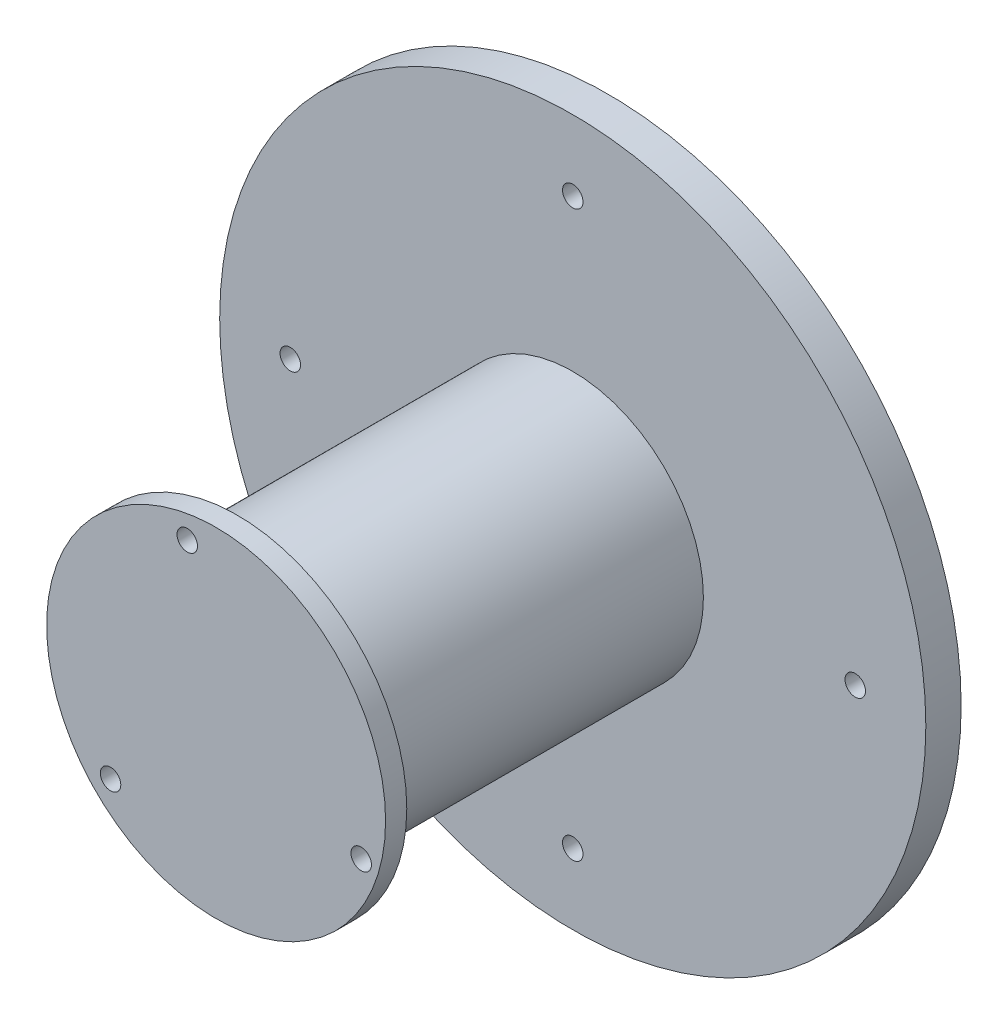
SolidWorks part; units mm, degrees
ref_plane "정면" through (0, 0, 0) normal (0, 0, 1) x (1, 0, 0)
ref_plane "윗면" through (0, 0, 0) normal (0, 1, 0) x (1, 0, 0)
ref_plane "우측면" through (0, 0, 0) normal (1, 0, 0) x (0, 0, -1)
sketch "스케치1" plane through (0, 0, 0) normal (0, 0, 1) x (1, 0, 0)
  line L0 (0, 18.5) -> (0, -18.5) construction
  line L1 (-18.5, 0) -> (18.5, 0) construction
  circle A0 centre (0, 0) radius 18.5
  dimension "D1" = 37
extrude "보스-돌출1" add sketch "스케치1" along normal blind 50
sketch "스케치2" plane through (0, 0, 0) normal (0, 0, -1) x (-1, 0, 0)
  circle A0 centre (0, 0) radius 50
  dimension "D1" = 100
extrude "보스-돌출2" add sketch "스케치2" along normal blind 5
sketch "스케치3" plane through (0, 0, -5) normal (0, 0, -1) x (-1, 0, 0)
  line L0 (0, 50) -> (0, -50) construction
  line L1 (-50, 0) -> (50, 0) construction
  circle A0 centre (0, 0) radius 50 construction
  circle A1 centre (0, 0) radius 25
  circle A2 centre (0, 0) radius 23
  dimension "D1" = 50
  dimension "D2" = 46
extrude "보스-돌출3" add sketch "스케치3" along normal blind 3
sketch "스케치4" plane through (0, 0, -5) normal (0, 0, -1) x (-1, 0, 0)
  circle A2 centre (-40, 0) radius 1.45
  circle A4 centre (40, 0) radius 1.45
  circle A5 centre (0, 40) radius 1.45
  circle A6 centre (0, -40) radius 1.45
  dimension "D2" = 2.9
  dimension "D3" = 2.9
extrude "컷-돌출1" cut sketch "스케치4" against normal blind 23 contours A2 | A5 | A4 | A6
sketch "스케치5" plane through (0, 0, 50) normal (0, 0, 1) x (1, 0, 0)
  circle A0 centre (-0.5045, 0.1153) radius 24
  point P15 (-0.5045, 0.1153)
  dimension "D1" = 48
extrude "보스-돌출4" add sketch "스케치5" against normal blind 3
sketch "스케치8" plane through (0, 0, 47) normal (0, 0, -1) x (-1, 0, 0)
  circle A3 centre (-20.0414, -6.2725) radius 1.522
  circle A4 centre (0, 0) radius 25
  circle A5 centre (4.5885, 20.4926) radius 1.522
  circle A7 centre (15.4528, -14.2201) radius 1.522
  point P11 (0, 0)
  point P16 (0, 0)
  dimension "D1" = 3
  dimension "D2" = 50
hole_wizard "M3.5 나사 구멍3" positions "스케치9" profile "스케치10" tap size "M3.5" standard "KS"
sketch "스케치9" plane through (0, 0, 47) normal (0, 0, -1) x (-1, 0, 0)
  point P0 (4.5885, 20.4926)
  point P3 (15.4528, -14.2201)
  point P6 (-20.0414, -6.2725)
sketch "스케치10" plane through (-4.5885, 20.4926, 47) normal (1, 0, 0) x (0, 1, 0)
  line L0 (0, 0) -> (0, 10.8712)
  line L1 (0, 10.8712) -> (1.45, 10)
  line L2 (1.45, 10) -> (1.45, 0.325)
  line L3 (1.45, 0.325) -> (1.775, 0)
  line L5 (1.775, 0) -> (0, 0)
  line L6 (-1.45, 0.325) -> (-1.775, 0) construction
  line L10 (0, 10.8712) -> (-1.45, 10) construction
  line L11 (0, -6.35) -> (0, 107.95) construction
  dimension "탭 드릴 지름" = 2.9
  dimension "탭 드릴 깊이" = 10
  dimension "표면 카운터싱크 지름" = 3.55
  dimension "표면 카운터싱크 각도" = 90
  dimension "드릴 각도" = 118
cosmetic thread "구멍 나사산4" parameters "D1"=7, "D2"=3.5
cosmetic thread "구멍 나사산5" parameters "D1"=7, "D2"=3.5
cosmetic thread "구멍 나사산6" parameters "D1"=7, "D2"=3.5
